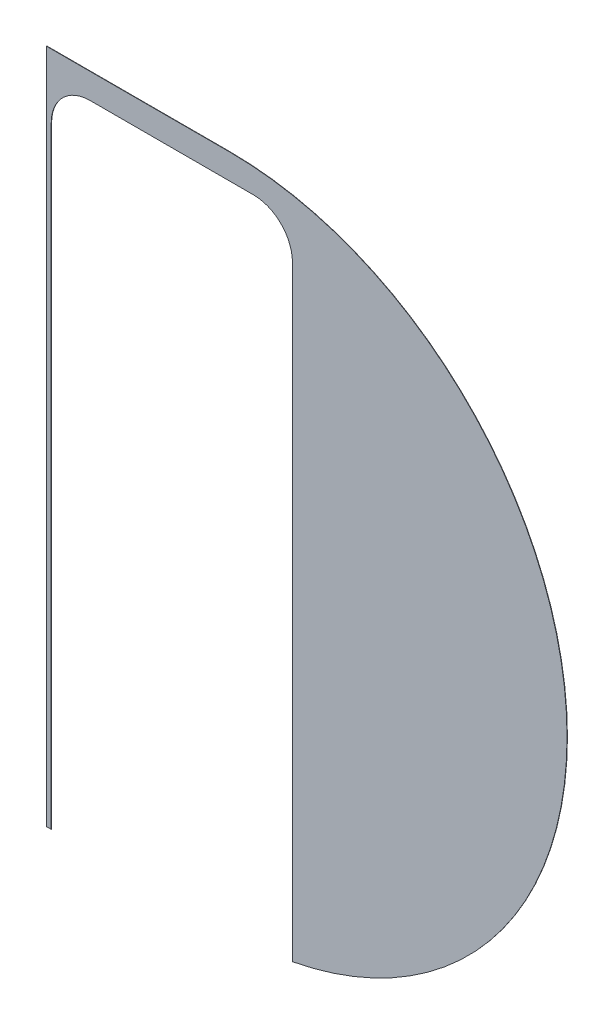
SolidWorks part; units mm, degrees
ref_plane "Front Plane" through (0, 0, 0) normal (0, 0, 1) x (1, 0, 0)
ref_plane "Top Plane" through (0, 0, 0) normal (0, 1, 0) x (1, 0, 0)
ref_plane "Right Plane" through (0, 0, 0) normal (1, 0, 0) x (0, 0, -1)
sketch "Sketch1" plane through (0, 0, 0) normal (0, 0, 1) x (1, 0, 0)
  line L1 (0, 0) -> (470, 0)
  line L2 (0, 0) -> (0, 1740)
  line L3 (0, 1740) -> (470, 1740)
  line L4 (470, 0) -> (470, 1740) construction
  arc A0 (470, 1740) -> (470, 0) centre (470, 870) cw
  dimension "D1" = 470
  dimension "D2" = 1740
extrude "Boss-Extrude1" add sketch "Sketch1" along normal blind 1
extrude "Cut-Extrude2" cut sketch "Sketch3" against normal blind 330
sketch "Sketch3" plane through (-1354.1121, -994.4575, -32) normal (0, 0, -1) x (-1, 0, 0)
  line L1 (-1887.1121, 819.4575) -> (-1466.1121, 819.4575)
  line L2 (-1987.1121, 919.4575) -> (-1987.1121, 2569.4575)
  line L3 (-1887.1121, 2669.4575) -> (-1466.1121, 2669.4575)
  line L4 (-1366.1121, 919.4575) -> (-1366.1121, 2569.4575)
  arc A0 (-1466.1121, 819.4575) -> (-1366.1121, 919.4575) centre (-1466.1121, 919.4575) ccw
  arc A1 (-1887.1121, 819.4575) -> (-1987.1121, 919.4575) centre (-1887.1121, 919.4575) cw
  arc A2 (-1466.1121, 2669.4575) -> (-1366.1121, 2569.4575) centre (-1466.1121, 2569.4575) cw
  arc A3 (-1987.1121, 2569.4575) -> (-1887.1121, 2669.4575) centre (-1887.1121, 2569.4575) cw
